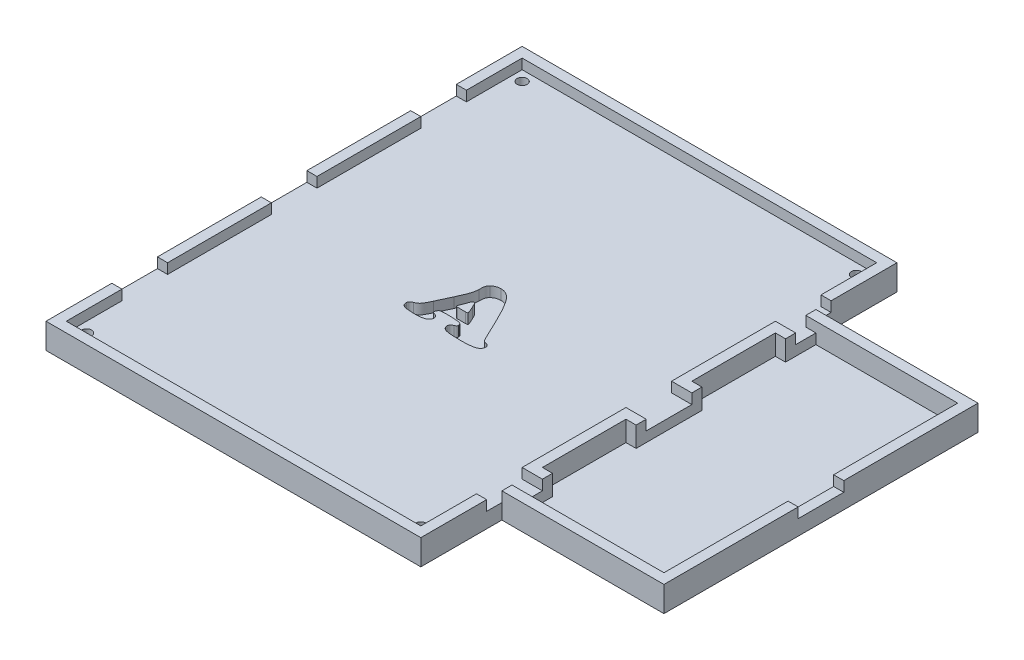
SolidWorks part; units mm, degrees
ref_plane "Front Plane" through (0, 0, 0) normal (0, 0, 1) x (1, 0, 0)
ref_plane "Top Plane" through (0, 0, 0) normal (0, 1, 0) x (1, 0, 0)
ref_plane "Right Plane" through (0, 0, 0) normal (1, 0, 0) x (0, 0, -1)
sketch "Sketch1" plane through (0, 0, 0) normal (0, 1, 0) x (1, 0, 0)
  line L1 (-37, 47) -> (37, 47)
  line L2 (-37, 47) -> (-37, -47)
  line L3 (-37, -47) -> (37, -47)
  line L4 (37, 47) -> (37, -47)
  line L5 (-37, 47) -> (37, -47) construction
  line L6 (-37, -47) -> (37, 47) construction
  point P0 (0, 0)
  point P5 (0, 0)
  dimension "D1" = 94
  dimension "D2" = 74
extrude "Boss-Extrude2" add sketch "Sketch1" along normal blind 5
sketch "Sketch4" plane through (0, 5, 0) normal (0, 1, 0) x (1, 0, 0)
  line L8 (35, -45) -> (35, 45)
  line L9 (35, 45) -> (-35, 45)
  line L10 (-35, 45) -> (-35, -45)
  line L11 (-35, -45) -> (35, -45)
  line L12 (35, -45) -> (35, 45)
  line L13 (35, 45) -> (-35, 45)
  line L14 (-35, 45) -> (-35, -45)
  line L15 (-35, -45) -> (35, -45)
  dimension "D1" = 2
extrude "Cut-Extrude2" cut sketch "Sketch4" against normal blind 2
sketch "Sketch5" plane through (0, 3, 0) normal (0, 1, 0) x (1, 0, 0)
  line L0 (-34, 0) -> (34, 0) construction
  line L18 (-34, -44) -> (34, -44)
  line L19 (34, -44) -> (34, 44)
  line L20 (-34, 44) -> (-34, -44)
  line L21 (34, 44) -> (-34, 44)
  line L22 (-34, -44) -> (34, -44)
  line L23 (34, -44) -> (34, 44)
  line L24 (-34, 44) -> (-34, -44)
  line L25 (34, 44) -> (-34, 44)
  circle A0 centre (-33, 43) radius 1
  circle A1 centre (33, 43) radius 1
  circle A2 centre (-33, -43) radius 1
  circle A3 centre (33, -43) radius 1
  dimension "D2" = 2
  dimension "D1" = 1
extrude "Cut-Extrude3" cut sketch "Sketch5" against normal through all both and the other way through all contours A1 | A3 | A2 | A0
sketch "Sketch6" plane through (0, 5, 0) normal (0, 1, 0) x (1, 0, 0)
  line L0 (35, -45) -> (35, 45) construction
  line L1 (35, 34) -> (37, 34)
  line L2 (35, 34) -> (35, 25)
  line L3 (35, 25) -> (37, 25)
  line L4 (37, 34) -> (37, 25)
  line L5 (37, -47) -> (37, 47) construction
  line L6 (35, 45) -> (-35, 45) construction
  line L7 (-35, 0) -> (35, 0) construction
  line L8 (-35, 45) -> (-35, -45) construction
  line L9 (35, -45) -> (35, 45) construction
  line L10 (35, -25) -> (37, -25)
  line L11 (37, -34) -> (37, -25)
  line L12 (35, -34) -> (37, -34)
  line L13 (35, -34) -> (35, -25)
  line L14 (37, 47) -> (-37, 47) construction
  line L15 (35, 4.5) -> (37, 4.5)
  line L16 (35, 4.5) -> (35, -4.5)
  line L17 (35, -4.5) -> (37, -4.5)
  line L18 (37, 4.5) -> (37, -4.5)
  line L19 (0, 47) -> (0, -47) construction
  line L20 (-37, -47) -> (37, -47) construction
  line L21 (-35, -34) -> (-35, -25)
  line L22 (-35, -34) -> (-37, -34)
  line L23 (-37, -34) -> (-37, -25)
  line L24 (-35, -25) -> (-37, -25)
  line L25 (-35, -4.5) -> (-37, -4.5)
  line L26 (-37, 4.5) -> (-37, -4.5)
  line L27 (-35, 4.5) -> (-37, 4.5)
  line L28 (-35, 4.5) -> (-35, -4.5)
  line L29 (-35, 25) -> (-37, 25)
  line L30 (-37, 34) -> (-37, 25)
  line L31 (-35, 34) -> (-37, 34)
  line L32 (-35, 34) -> (-35, 25)
  point P24 (35, 0)
  dimension "D1" = 11
  dimension "D2" = 9
  dimension "D3" = 9
extrude "Cut-Extrude5" cut sketch "Sketch6" against normal up to surface (2 mm away) up to face at (-33, 3, -42)
sketch "Sketch7" plane through (0, 0, 0) normal (0, 1, 0) x (1, 0, 0)
  line L0 (37, -47) -> (37, 47) construction
  line L1 (37, 31) -> (69, 31)
  line L2 (37, 31) -> (37, -31)
  line L3 (37, -31) -> (69, -31)
  line L4 (69, 31) -> (69, -31)
  point P6 (69, 0)
  dimension "D1" = 62
  dimension "D2" = 32
extrude "Boss-Extrude3" add sketch "Sketch7" along normal up to surface (5 mm away) up to face at (36, 5, 14.75)
sketch "Sketch10" plane through (0, 5, 0) normal (0, 1, 0) x (1, 0, 0)
  line L24 (39, -6.5) -> (37, -6.5)
  line L25 (37, -6.5) -> (37, -23)
  line L26 (37, -23) -> (39, -23)
  line L27 (39, -23) -> (39, -29)
  line L28 (39, -29) -> (67, -29)
  line L29 (67, -29) -> (67, 29)
  line L30 (67, 29) -> (39, 29)
  line L31 (39, 29) -> (39, 23)
  line L32 (39, 23) -> (37, 23)
  line L33 (37, 23) -> (37, 6.5)
  line L34 (37, 6.5) -> (39, 6.5)
  line L35 (39, 6.5) -> (39, -6.5)
  line L36 (39, -6.5) -> (37, -6.5)
  line L37 (37, -6.5) -> (37, -23)
  line L38 (37, -23) -> (39, -23)
  line L39 (39, -23) -> (39, -29)
  line L40 (39, -29) -> (67, -29)
  line L41 (67, -29) -> (67, 29)
  line L42 (67, 29) -> (39, 29)
  line L43 (39, 29) -> (39, 23)
  line L44 (39, 23) -> (37, 23)
  line L45 (37, 23) -> (37, 6.5)
  line L46 (37, 6.5) -> (39, 6.5)
  line L47 (39, 6.5) -> (39, -6.5)
  point P0 (0, 0)
  dimension "D1" = 2
extrude "Cut-Extrude6" cut sketch "Sketch10" against normal blind 4
sketch "Sketch11" plane through (0, 5, 0) normal (0, 1, 0) x (1, 0, 0)
  line L0 (39, 6.5) -> (39, -6.5) construction
  line L1 (37, 4.5) -> (39, 4.5)
  line L2 (37, 4.5) -> (37, -4.5)
  line L3 (37, -4.5) -> (39, -4.5)
  line L4 (39, 4.5) -> (39, -4.5)
extrude "Cut-Extrude7" cut sketch "Sketch11" against normal up to surface (2 mm away) up to face at (-33, 3, -42)
sketch "Sketch12" plane through (0, 5, 0) normal (0, 1, 0) x (1, 0, 0)
  line L1 (37, -25) -> (39, -25)
  line L2 (37, -25) -> (37, -29)
  line L3 (37, -29) -> (39, -29)
  line L4 (39, -25) -> (39, -29)
  line L5 (39, 29) -> (37, 29)
  line L6 (39, 29) -> (39, 25)
  line L7 (39, 25) -> (37, 25)
  line L8 (37, 29) -> (37, 25)
extrude "Cut-Extrude8" cut sketch "Sketch12" against normal up to surface (2 mm away) up to face at (-33, 3, -42)
sketch "Sketch13" plane through (0, 5, 0) normal (0, 1, 0) x (1, 0, 0)
  line L0 (67, -29) -> (67, 29) construction
  line L1 (67, 4.5) -> (69, 4.5)
  line L2 (67, 4.5) -> (67, -4.5)
  line L3 (67, -4.5) -> (69, -4.5)
  line L4 (69, 4.5) -> (69, -4.5)
  line L5 (69, -31) -> (69, 31) construction
  point P8 (67, 0)
  dimension "D1" = 9
extrude "Cut-Extrude10" cut sketch "Sketch13" against normal up to surface (2 mm away) up to face at (-33, 3, -42)
sketch "Sketch16" plane through (0, 3, 0) normal (0, 1, 0) x (1, 0, 0)
  text T0 "A" font "Cooper Black" height in points 50
extrude "Cut-Extrude11" cut sketch "Sketch16" against normal up to surface (2 mm away) up to face at (43, 1, 0)
